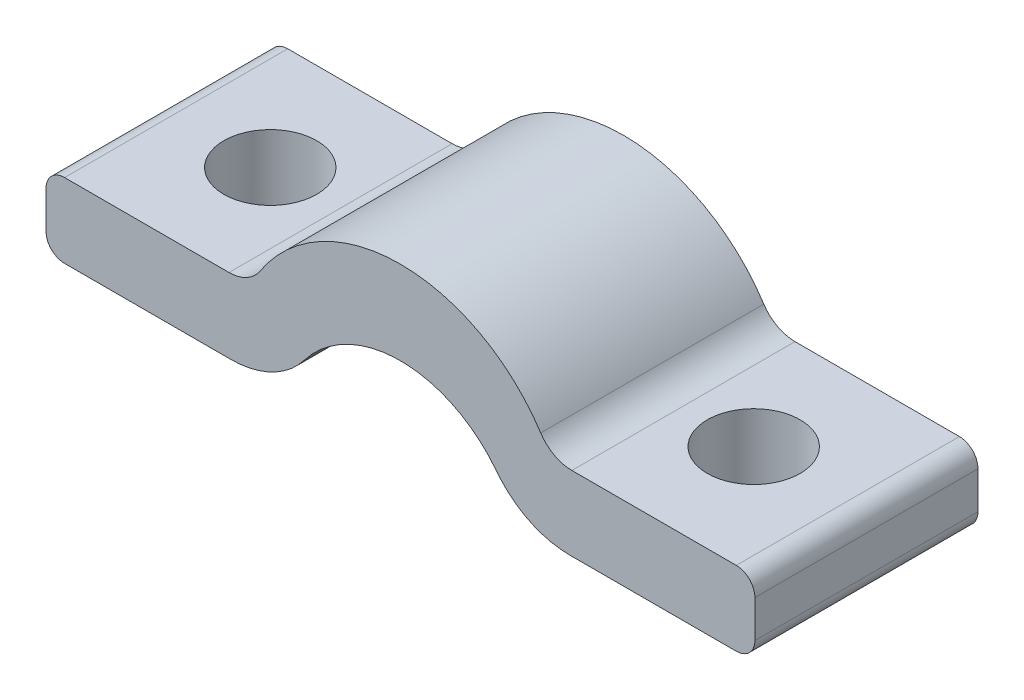
SolidWorks part; units mm, degrees
ref_plane "Front Plane" through (0, 0, 0) normal (0, 0, 1) x (1, 0, 0)
ref_plane "Top Plane" through (0, 0, 0) normal (0, 1, 0) x (1, 0, 0)
ref_plane "Right Plane" through (0, 0, 0) normal (1, 0, 0) x (0, 0, -1)
sketch "Sketch1" plane through (0, 0, 0) normal (0, 0, 1) x (1, 0, 0)
  line L0 (-3.0923, 1) -> (-9.5311, 1)
  line L1 (-9.5311, 1) -> (-9.5311, 3)
  line L2 (-9.5311, 3) -> (-4.0311, 3)
  line L3 (3.0923, 1) -> (9.5311, 1)
  line L4 (9.5311, 1) -> (9.5311, 3)
  line L5 (9.5311, 3) -> (4.0311, 3)
  circle A0 centre (0, 0) radius 3.25 construction
  arc A1 (-3.0923, 1) -> (3.0923, 1) centre (0, 0) cw
  arc A2 (-4.0311, 3) -> (4.0311, 3) centre (0, 1) cw
  dimension "D1" = 6.5
  dimension "D4" = 4.5
  dimension "D2" = 1
  dimension "D3" = 2
  dimension "D5" = 5.5
  dimension "D6" = 5.5
  dimension "D7" = 2
  dimension "D8" = 1
extrude "Boss-Extrude1" add sketch "Sketch1" along normal blind 6
sketch "Sketch2" plane through (0, 3, 0) normal (0, 1, 0) x (1, 0, 0)
  line L0 (6.5, -3) -> (9.5311, -3) construction
  line L1 (9.5311, -6) -> (9.5311, 0) construction
  line L2 (-6.5, -3) -> (6.5, -3) construction
  line L3 (-6.5, -3) -> (-9.5311, -3) construction
  line L4 (-9.5311, -6) -> (-9.5311, 0) construction
  circle A0 centre (-6.5, -3) radius 1.25
  circle A1 centre (6.5, -3) radius 1.25
  dimension "D1" = 2.5
  dimension "D2" = 13
extrude "Cut-Extrude1" cut sketch "Sketch2" against normal blind 10
fillet "Fillet1" radius 1 2 edges at (4.0311, 3, 3) (-4.0311, 3, 3)
fillet "Fillet2" radius 0.5 4 edges at (9.5311, 1, 3) (9.5311, 3, 3) (-9.5311, 1, 3) (-9.5311, 3, 3)
fillet "Fillet3" radius 2.5 2 edges at (3.0923, 1, 3) (-3.0923, 1, 3)
